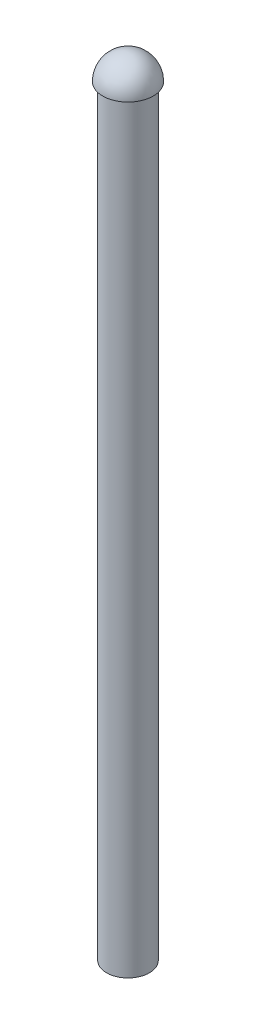
SolidWorks part; units mm, degrees
material "Brass"
ref_plane "Front Plane" through (0, 0, 0) normal (0, 0, 1) x (1, 0, 0)
ref_plane "Top Plane" through (0, 0, 0) normal (0, 1, 0) x (1, 0, 0)
ref_plane "Right Plane" through (0, 0, 0) normal (1, 0, 0) x (0, 0, -1)
sketch "Sketch1" plane through (0, 0, 0) normal (0, 1, 0) x (1, 0, 0)
  circle A0 centre (0, 0) radius 0.7144
  dimension "D1" = 1.4287
extrude "Boss-Extrude1" add sketch "Sketch1" along normal blind 25.4
sketch "Sketch2" plane through (0, 25.4, 0) normal (0, 1, 0) x (1, 0, 0)
  line L0 (-0.0162, 0.8412) -> (0.0162, -0.8412)
  arc A0 (-0.0162, 0.8412) -> (0.0162, -0.8412) centre (0, 0) ccw
  dimension "D1" = 1.6827
revolve "Revolve1" add sketch "Sketch2" angle 180 about L0
